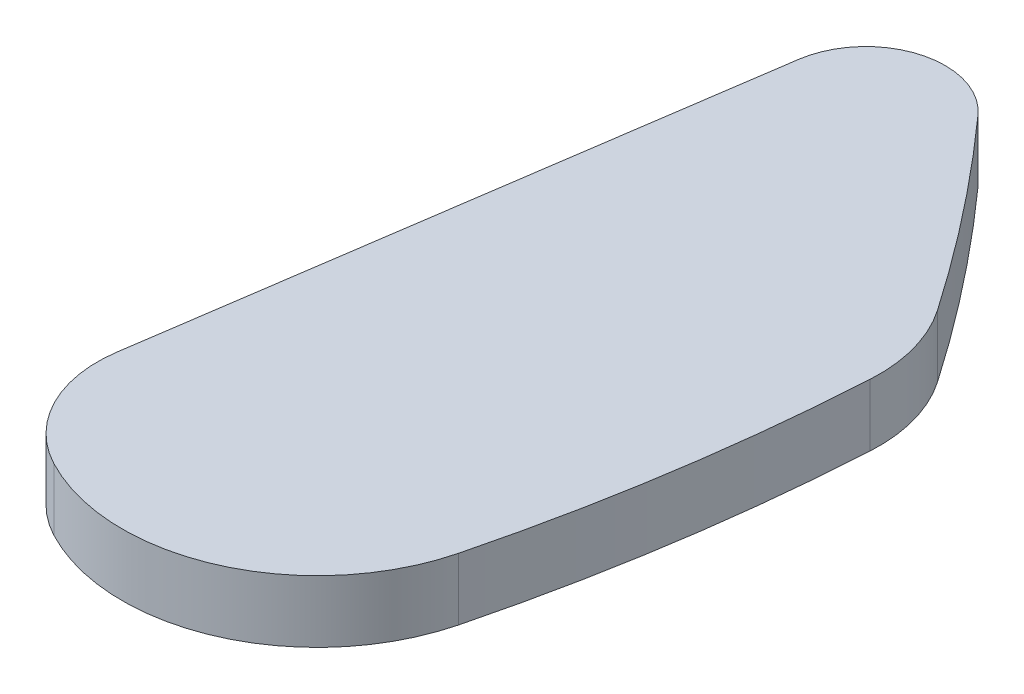
SolidWorks part; units mm, degrees
ref_plane "Front Plane" through (0, 0, 0) normal (0, 0, 1) x (1, 0, 0)
ref_plane "Top Plane" through (0, 0, 0) normal (0, 1, 0) x (1, 0, 0)
ref_plane "Right Plane" through (0, 0, 0) normal (1, 0, 0) x (0, 0, -1)
sketch "Sketch1" plane through (0, 0, 0) normal (0, 1, 0) x (1, 0, 0)
  line L44 (-43.1946, 148.7152) -> (-50.2252, 100.8707)
  arc A149 (-22.4566, 100.5997) -> (-18.0206, 129.2968) centre (-171.2572, 138.2924) ccw
  arc A150 (-18.0206, 129.2968) -> (-20.1164, 136.8055) centre (-30, 130) ccw
  arc A151 (-20.1164, 136.8055) -> (-32.0981, 152.0476) centre (-146.5445, 49.7519) ccw
  arc A152 (-32.0981, 152.0476) -> (-43.1946, 148.7152) centre (-36.8667, 147.7853) ccw
  arc A158 (-22.4566, 100.5997) -> (-45.0004, 90.5736) centre (-37.6721, 104.4539) cw
  arc A159 (-50.2252, 100.8707) -> (-45.0004, 90.5736) centre (-40.3315, 99.4168) ccw
  dimension "D3" = 12
  dimension "D1" = 10
extrude "Boss-Extrude2" add sketch "Sketch1" along normal blind 5
